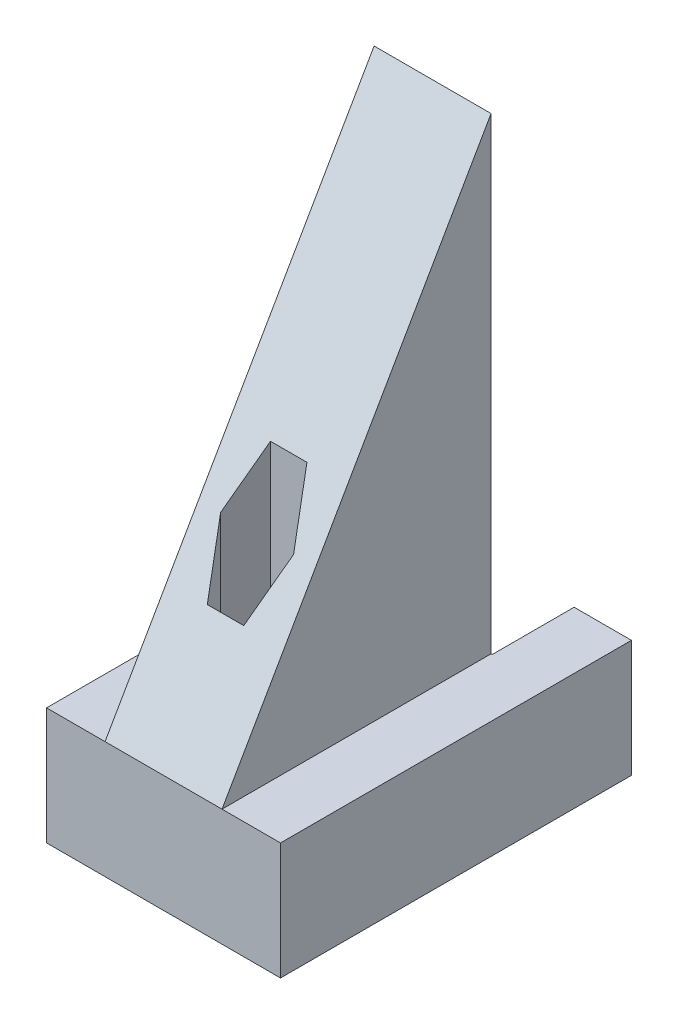
SolidWorks part; units mm, degrees
ref_plane "Front Plane" through (0, 0, 0) normal (0, 0, 1) x (1, 0, 0)
ref_plane "Top Plane" through (0, 0, 0) normal (0, 1, 0) x (1, 0, 0)
ref_plane "Right Plane" through (0, 0, 0) normal (1, 0, 0) x (0, 0, -1)
sketch "Sketch1" plane through (0, 0, 0) normal (0, 1, 0) x (1, 0, 0)
  line L0 (-5.1, 15) -> (-5.1, 8)
  line L1 (10, -15) -> (-10, -15)
  line L2 (10, -15) -> (10, 15)
  line L3 (10, 15) -> (5.1, 15)
  line L4 (-10, -15) -> (-10, 15)
  line L5 (10, -15) -> (-10, 15) construction
  line L6 (10, 15) -> (-10, -15) construction
  line L7 (-5.1, 8) -> (5.1, 8)
  line L8 (5.1, 8) -> (5.1, 15)
  line L9 (-5.1, 15) -> (-10, 15)
  point P0 (0, 0)
  point P8 (0, 8)
  dimension "D1" = 30
  dimension "D2" = 7
  dimension "D3" = 10.2
  dimension "D4" = 20
extrude "Boss-Extrude1" add sketch "Sketch1" along normal blind 10
sketch "Sketch2" plane through (0, 0, 0) normal (1, 0, 0) x (0, 0, -1)
  line L0 (-15, 10) -> (8, 50)
  line L1 (8, 50) -> (8, 10)
  line L2 (-15, 10) -> (15, 10) construction
  line L3 (8, 10) -> (-15, 10)
  point P3 (0, 0)
  point P8 (8, 56.5769)
  dimension "D1" = 40
extrude "Boss-Extrude2" add sketch "Sketch2" along normal mid plane 10
sketch "Sketch3" plane through (0, 0, 0) normal (0, 1, 0) x (1, 0, 0)
  line L0 (-5.1, 15) -> (-10, 15) construction
  line L1 (3.1177, -7) -> (1.5588, -4.3)
  line L2 (1.5588, -4.3) -> (-1.5588, -4.3)
  line L3 (-1.5588, -4.3) -> (-3.1177, -7)
  line L4 (-3.1177, -7) -> (-1.5588, -9.7)
  line L5 (-1.5588, -9.7) -> (1.5588, -9.7)
  line L6 (1.5588, -9.7) -> (3.1177, -7)
  circle A0 centre (0, -7) radius 2.7 construction
  point P1 (0, 0)
  point P12 (1.6068, -9.6718)
  point P13 (3.1177, -7)
  dimension "D1" = 5.4
  dimension "D2" = 22
extrude "Cut-Extrude1" cut sketch "Sketch3" against normal blind 25 from offset 30
sketch "Sketch4" plane through (0, 0, 0) normal (0, 1, 0) x (1, 0, 0)
  circle A0 centre (0, -7) radius 1.4
  circle A1 centre (0, -7) radius 2.7 construction
  dimension "D1" = 2.8
extrude "Cut-Extrude2" cut sketch "Sketch4" along normal up to next
